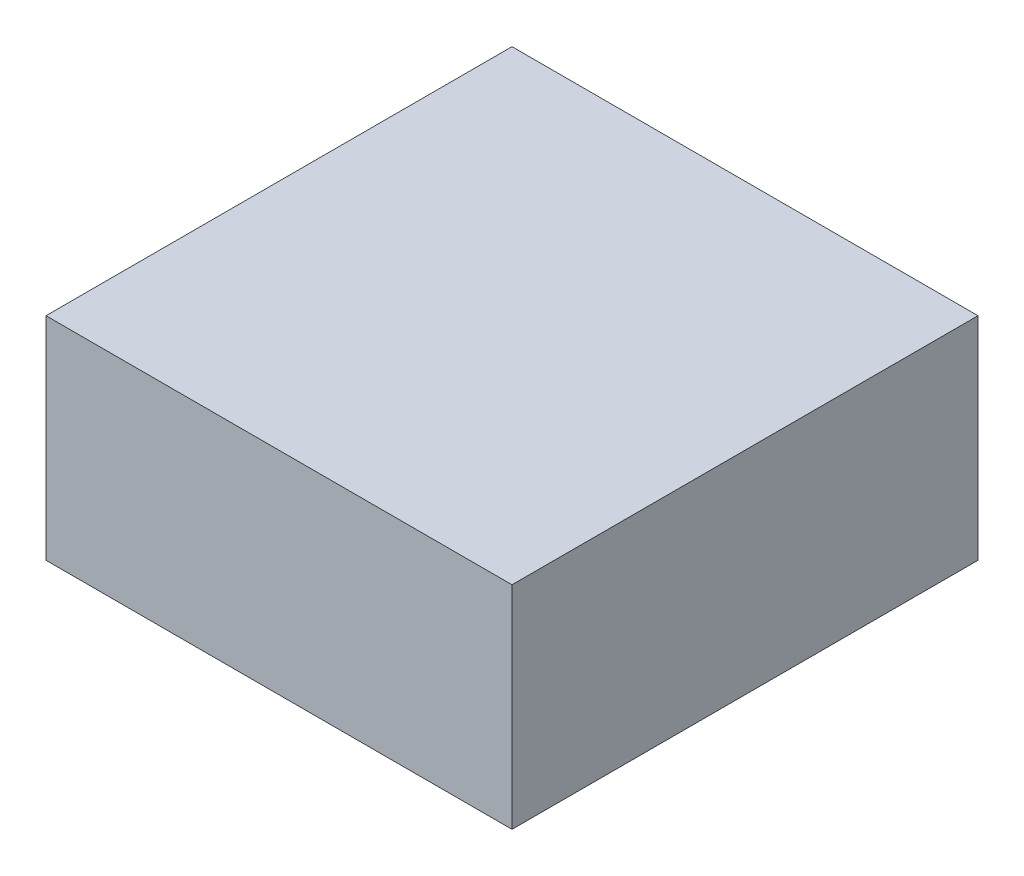
SolidWorks part; units mm, degrees
ref_plane "Front Plane" through (0, 0, 0) normal (0, 0, 1) x (1, 0, 0)
ref_plane "Top Plane" through (0, 0, 0) normal (0, 1, 0) x (1, 0, 0)
ref_plane "Right Plane" through (0, 0, 0) normal (1, 0, 0) x (0, 0, -1)
sketch "Sketch1" plane through (0, 0, 0) normal (0, 1, 0) x (1, 0, 0)
  line L1 (-139.7, 139.7) -> (139.7, 139.7)
  line L2 (-139.7, 139.7) -> (-139.7, -139.7)
  line L3 (-139.7, -139.7) -> (139.7, -139.7)
  line L4 (139.7, 139.7) -> (139.7, -139.7)
  line L5 (-139.7, 139.7) -> (139.7, -139.7) construction
  line L6 (-139.7, -139.7) -> (139.7, 139.7) construction
  point P0 (0, 0)
  dimension "D1" = 279.4
extrude "Boss-Extrude1" add sketch "Sketch1" along normal blind 127
